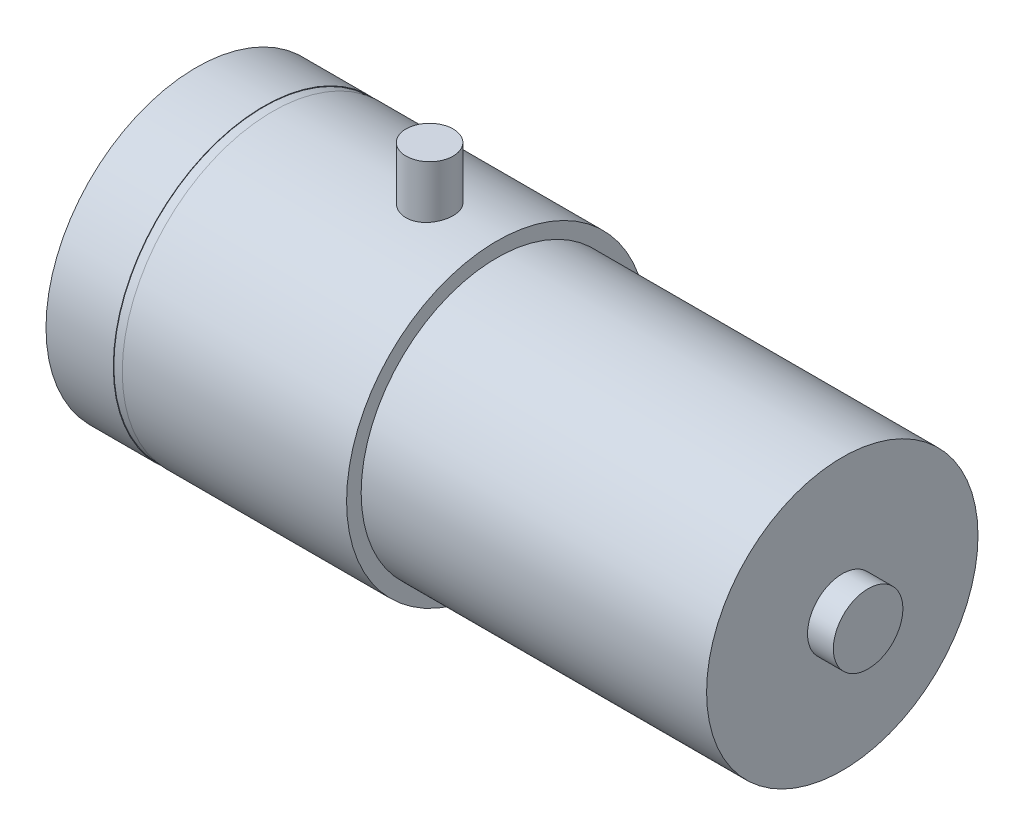
SolidWorks part; units mm, degrees
ref_plane "Plan de face" through (0, 0, 0) normal (0, 0, 1) x (1, 0, 0)
ref_plane "Plan de dessus" through (0, 0, 0) normal (0, 1, 0) x (1, 0, 0)
ref_plane "Plan de droite" through (0, 0, 0) normal (1, 0, 0) x (0, 0, -1)
sketch "Esquisse1" plane through (0, 0, 0) normal (0, 0, 1) x (1, 0, 0)
  line L0 (0, 0) -> (18.7332, 0) construction
  line L1 (-33.6, 0) -> (-33.6, 2.15)
  line L2 (-33.6, 2.15) -> (-26.8, 2.15)
  line L3 (-26.8, 2.15) -> (-26.8, 13.4)
  line L4 (-26.8, 13.4) -> (0, 13.4)
  line L5 (0, 13.4) -> (0, 12.1)
  line L6 (0, 12.1) -> (30.8, 12.1)
  line L7 (30.8, 12.1) -> (30.8, 3.1)
  line L8 (30.8, 3.1) -> (33.1, 3.1)
  line L9 (33.1, 3.1) -> (33.1, 0)
  line L10 (0, 12.1) -> (0, 0) construction
  line L11 (-33.6, 0) -> (33.1, 0)
  point P2 (0, 0)
  dimension "D1" = 2.15
  dimension "D2" = 6.8
  dimension "D3" = 26.8
  dimension "D4" = 57.6
  dimension "D5" = 2.3
  dimension "D6" = 13.4
  dimension "D7" = 12.1
  dimension "D8" = 3.1
revolve "Révolution1" add sketch "Esquisse1" angle 360 about L0
sketch "Esquisse2" plane through (0, 0, 0) normal (0, 1, 0) x (1, 0, 0)
  line L0 (0, -13.4) -> (0, 13.4) construction
  circle A0 centre (-6, 0) radius 2.1
  dimension "D1" = 4.2
  dimension "D2" = 6
extrude "Boss.-Extru.1" add sketch "Esquisse2" along normal blind 18
sketch "Esquisse3" plane through (-26.8, 0, 0) normal (-1, 0, 0) x (0, 0, 1)
  circle A0 centre (0, 0) radius 13.35
  circle A1 centre (0, 0) radius 13.4 construction
  circle A2 centre (0, 0) radius 13.4
  point P3 (0, 13.35)
  point P7 (0, 13.4)
  dimension "D1" = 0.05
extrude "Enlèv. mat.-Extru.1" cut sketch "Esquisse3" against normal blind 0.8 from offset 6
